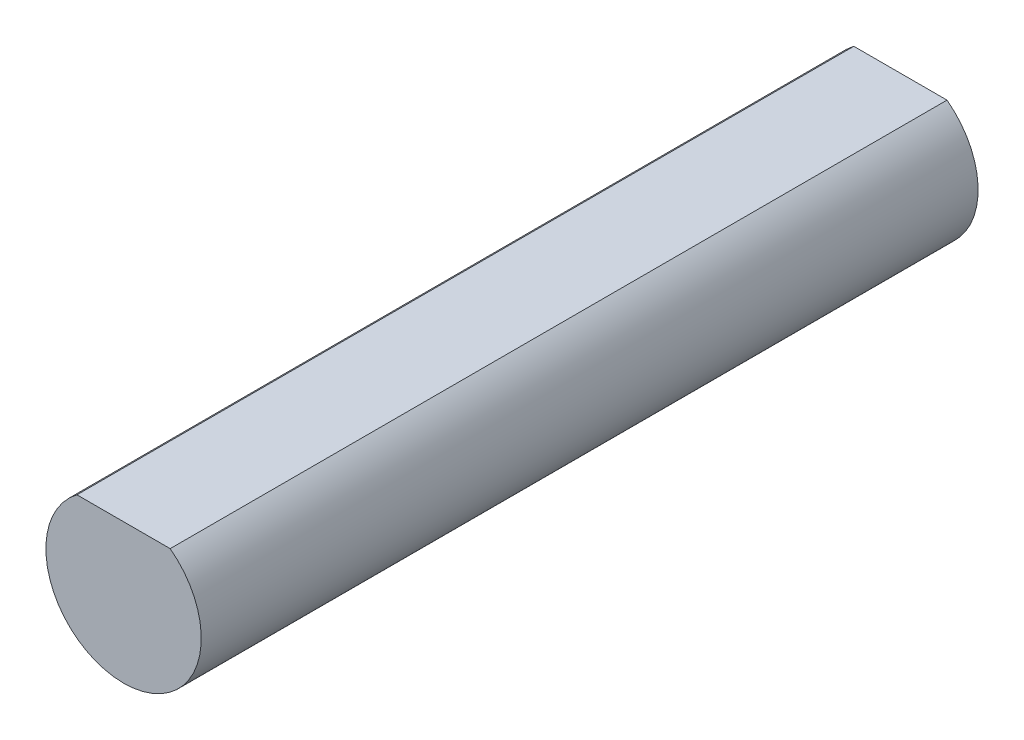
SolidWorks part; units mm, degrees
ref_plane "Front Plane" through (0, 0, 0) normal (0, 0, 1) x (1, 0, 0)
ref_plane "Top Plane" through (0, 0, 0) normal (0, 1, 0) x (1, 0, 0)
ref_plane "Right Plane" through (0, 0, 0) normal (1, 0, 0) x (0, 0, -1)
sketch "Sketch1" plane through (0, 0, 0) normal (0, 0, 1) x (1, 0, 0)
  line L0 (-1.5, 2) -> (3.2681, 2)
  arc A0 (-1.5, 2) -> (1.5, 2) centre (0, 0) ccw
  dimension "D1" = 5
  dimension "2" = 2
extrude "Boss-Extrude1" add sketch "Sketch1" along normal blind 25 contours L0 A0
